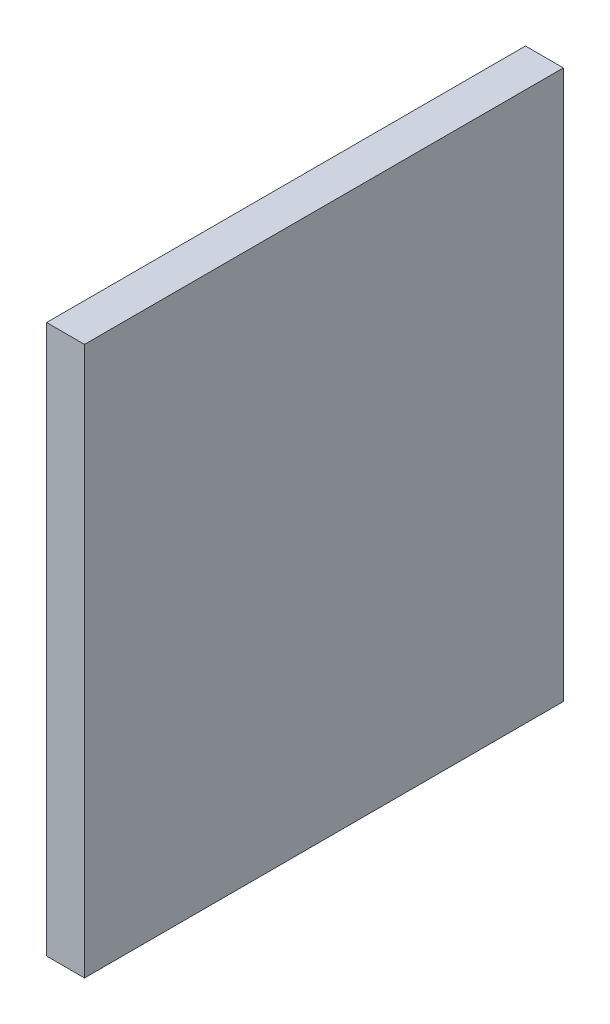
SolidWorks part; units mm, degrees
ref_plane "前视基准面" through (0, 0, 0) normal (0, 0, 1) x (1, 0, 0)
ref_plane "上视基准面" through (0, 0, 0) normal (0, 1, 0) x (1, 0, 0)
ref_plane "右视基准面" through (0, 0, 0) normal (1, 0, 0) x (0, 0, -1)
other "Configuration Table"
sketch "草图1" plane through (0, 0, 0) normal (1, 0, 0) x (0, 0, -1)
  line L1 (-56.4348, 18.3536) -> (-8.4348, 18.3536)
  line L2 (-56.4348, 18.3536) -> (-56.4348, -36.6464)
  line L3 (-56.4348, -36.6464) -> (-8.4348, -36.6464)
  line L4 (-8.4348, 18.3536) -> (-8.4348, -36.6464)
  dimension "D1" = 55
  dimension "D2" = 48
extrude "凸台-拉伸1" add sketch "草图1" along normal blind 3.8 contours L2 L1 L4 L3
